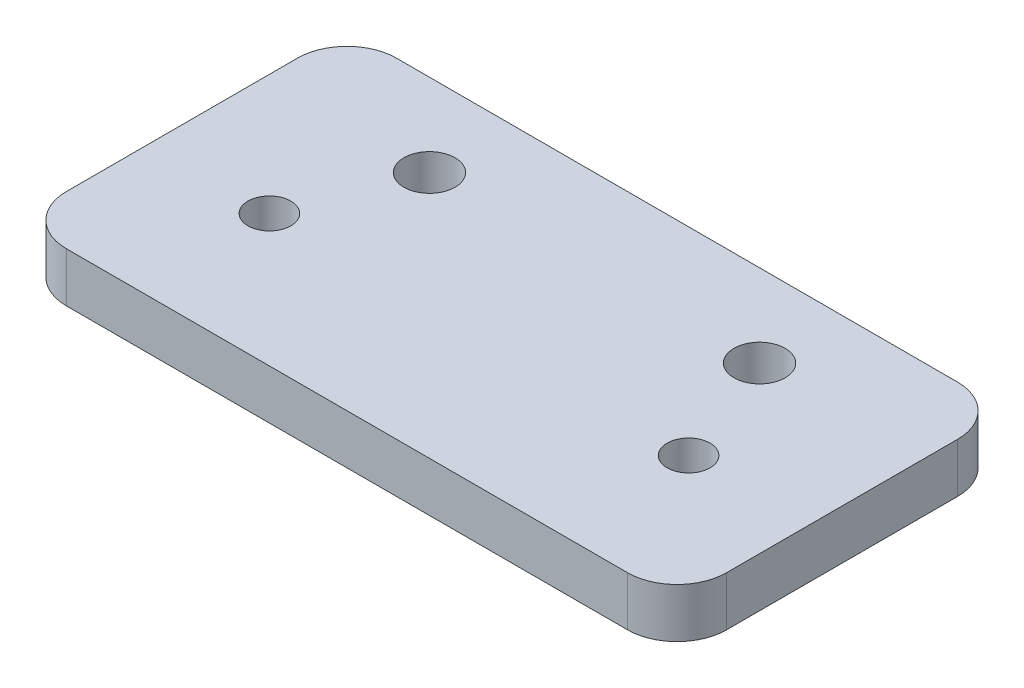
SolidWorks part; units mm, degrees
ref_plane "前视基准面" through (0, 0, 0) normal (0, 0, 1) x (1, 0, 0)
ref_plane "上视基准面" through (0, 0, 0) normal (0, 1, 0) x (1, 0, 0)
ref_plane "右视基准面" through (0, 0, 0) normal (1, 0, 0) x (0, 0, -1)
sketch "草图1" plane through (0, 0, 0) normal (0, 1, 0) x (1, 0, 0)
  line L1 (-20, -15) -> (20, -15)
  line L2 (-20, -15) -> (-20, 15)
  line L3 (-20, 15) -> (20, 15)
  line L4 (20, -15) -> (20, 15)
  line L5 (-20, -15) -> (20, 15) construction
  line L6 (-20, 15) -> (20, -15) construction
  point P0 (0, 0)
  dimension "D1" = 40
  dimension "D2" = 30
extrude "凸台-拉伸1" add sketch "草图1" along normal blind 3
sketch "草图2" plane through (0, 3, 0) normal (0, 1, 0) x (1, 0, 0)
  line L0 (-20, 0) -> (20, 0) construction
  line L1 (-20, 15) -> (-20, -15) construction
  line L2 (20, -15) -> (20, 15) construction
  line L3 (-20, -15) -> (20, -15) construction
  line L4 (0, 15) -> (0, -15) construction
  line L5 (20, 15) -> (-20, 15) construction
  circle A0 centre (-10, 0) radius 1.55
  circle A1 centre (10, 0) radius 1.55
  dimension "D1" = 3.1
  dimension "D2" = 10
extrude "切除-拉伸1" cut sketch "草图2" against normal through all
sketch "草图3" plane through (0, 3, 0) normal (0, 1, 0) x (1, 0, 0)
  line L0 (20, -15) -> (20, 15) construction
  line L1 (-20, 15) -> (20, 15)
  line L2 (-20, 15) -> (-20, 5)
  line L3 (-20, 5) -> (20, 5)
  line L4 (20, 15) -> (20, 5)
  dimension "D1" = 10
extrude "切除-拉伸2" cut sketch "草图3" against normal through all
fillet "圆角2" radius 3 4 edges at (20, 1.5, 15) (-20, 1.5, 15) (20, 1.5, -5) (-20, 1.5, -5)
sketch "草图4" plane through (0, 3, 0) normal (0, 1, 0) x (1, 0, 0)
  line L0 (0, 5) -> (0, -15) construction
  line L1 (-17, 5) -> (17, 5) construction
  line L2 (-17, -15) -> (17, -15) construction
  circle A0 centre (-12.7, -7) radius 1.3
  circle A1 centre (12.7, -7) radius 1.3
  dimension "D1" = 12
  dimension "D2" = 2.6
  dimension "D3" = 12.7
extrude "切除-拉伸3" cut sketch "草图4" against normal through all
